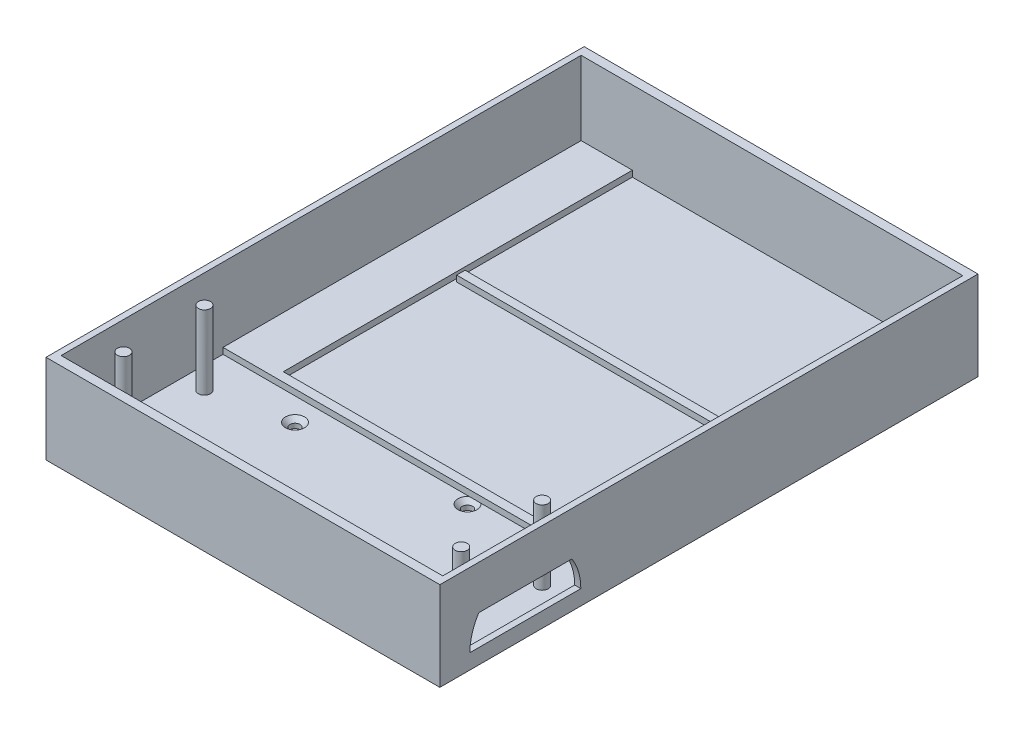
SolidWorks part; units mm, degrees
ref_plane "Front Plane" through (0, 0, 0) normal (0, 0, 1) x (1, 0, 0)
ref_plane "Top Plane" through (0, 0, 0) normal (0, 1, 0) x (1, 0, 0)
ref_plane "Right Plane" through (0, 0, 0) normal (1, 0, 0) x (0, 0, -1)
sketch "Sketch1" plane through (0, 0, 0) normal (0, 1, 0) x (1, 0, 0)
  line L0 (108.1468, 39.1756) -> (131.5768, 39.1756)
  line L1 (23.9468, 39.1756) -> (108.1468, 39.1756)
  line L2 (23.9468, 39.1756) -> (23.9468, -17.2844)
  line L3 (23.9468, -17.2844) -> (108.1468, -17.2844)
  line L4 (108.1468, 39.1756) -> (108.1468, -17.2844)
  line L5 (23.9468, 39.1756) -> (6.9568, 39.1756)
  line L6 (6.9568, 39.1756) -> (131.5768, 39.1756)
  line L7 (6.9568, 39.1756) -> (3.9568, 39.1756)
  line L8 (131.5768, 39.1756) -> (134.5768, 39.1756)
  line L9 (134.5768, 39.1756) -> (134.5768, 42.1756)
  line L10 (3.9568, 39.1756) -> (134.5768, 39.1756)
  line L11 (3.9568, 39.1756) -> (3.9568, -17.083)
  line L12 (3.9568, -17.083) -> (134.5768, -17.083)
  line L13 (134.5768, 39.1756) -> (134.5768, -17.083)
  line L14 (3.9568, -17.083) -> (3.9568, -20.083)
  line L15 (134.5768, 42.1756) -> (3.9568, 42.1756)
  line L16 (134.5768, 42.1756) -> (134.5768, 39.1756)
  line L17 (134.5768, 39.1756) -> (3.9568, 39.1756)
  line L18 (3.9568, 42.1756) -> (3.9568, 39.1756)
  line L19 (3.9568, -20.083) -> (3.9568, -76.583)
  line L20 (3.9568, -17.083) -> (134.5768, -17.083)
  line L21 (3.9568, -17.083) -> (3.9568, -20.083)
  line L22 (3.9568, -20.083) -> (134.5768, -20.083)
  line L23 (134.5768, -17.083) -> (134.5768, -20.083)
  line L24 (23.9468, 39.1756) -> (23.9468, -76.583)
  line L25 (3.9568, -76.583) -> (134.5768, -76.583)
  line L26 (3.9568, -76.583) -> (3.9568, -20.083)
  line L27 (3.9568, -20.083) -> (134.5768, -20.083)
  line L28 (134.5768, -76.583) -> (134.5768, -20.083)
  line L29 (3.9568, -76.583) -> (134.5768, -76.583)
  line L30 (3.9568, -76.583) -> (3.9568, -79.583)
  line L31 (3.9568, -79.583) -> (134.5768, -79.583)
  line L32 (134.5768, -76.583) -> (134.5768, -79.583)
  line L33 (3.9568, -79.583) -> (134.5768, -79.583)
  line L34 (3.9568, -79.583) -> (3.9568, -133.283)
  line L35 (3.9568, -133.283) -> (134.5768, -133.283)
  line L36 (134.5768, -79.583) -> (134.5768, -133.283)
  line L37 (3.9568, -133.283) -> (134.5768, -133.283)
  line L38 (3.9568, -133.283) -> (3.9568, -136.283)
  line L39 (3.9568, -136.283) -> (134.5768, -136.283)
  line L40 (134.5768, -133.283) -> (134.5768, -136.283)
  line L41 (108.1468, -17.2844) -> (108.1468, -76.583)
  line L42 (108.1468, -67.5003) -> (109.1468, -67.5003)
  line L43 (108.1468, 39.1756) -> (109.1468, 39.1756)
  line L44 (108.1468, 39.1756) -> (108.1468, -76.583)
  line L45 (108.1468, -76.583) -> (109.1468, -76.583)
  line L46 (109.1468, 39.1756) -> (109.1468, -76.583)
  line L47 (23.9468, -33.892) -> (22.9468, -33.892)
  line L48 (109.1468, -76.583) -> (134.5768, -76.583)
  line L49 (109.1468, -76.583) -> (109.1468, 39.1756)
  line L50 (109.1468, 39.1756) -> (134.5768, 39.1756)
  line L51 (134.5768, -76.583) -> (134.5768, 39.1756)
  line L52 (23.9468, -76.583) -> (22.9468, -76.583)
  line L53 (23.9468, -76.583) -> (23.9468, 39.1756)
  line L54 (23.9468, 39.1756) -> (22.9468, 39.1756)
  line L55 (22.9468, -76.583) -> (22.9468, 39.1756)
  line L57 (109.1468, 39.1756) -> (134.5768, 39.1756)
  line L58 (109.1468, 39.1756) -> (109.1468, -76.583)
  line L59 (109.1468, -76.583) -> (134.5768, -76.583)
  line L60 (134.5768, 39.1756) -> (134.5768, -76.583)
  line L61 (3.9568, 39.1756) -> (22.9468, 39.1756)
  line L62 (3.9568, 39.1756) -> (3.9568, -76.583)
  line L63 (3.9568, -76.583) -> (22.9468, -76.583)
  line L64 (22.9468, 39.1756) -> (22.9468, -76.583)
  dimension "D1" = 84.2
  dimension "D2" = 56.46
  dimension "D3" = 23.43
  dimension "D4" = 16.99
  dimension "D5" = 3
  dimension "D6" = 3
  dimension "D7" = 3
  dimension "D8" = 3
  dimension "D9" = 56.5
  dimension "D10" = 3
  dimension "D11" = 53.7
  dimension "D12" = 3
  dimension "D13" = 1
  dimension "D14" = 1
extrude "Boss-Extrude1" add sketch "Sketch1" along normal blind 2 contours L40 L35 L38 L39 | L32 L25 L29 L30 L31 | L22 L46 L25 L28 | L25 L55 L22 L19 | L12 L55 L17 L7 L11 | L17 L46 L20 L13 L8 | L22 L55 L12 L14 | L20 L46 L22 L23 | L41 L3 L24 L22 | L15 L18 L7 L17 L5 L1 L0 L8 L9
sketch "Sketch2" plane through (0, 0, 0) normal (0, -1, 0) x (1, 0, 0)
  line L1 (3.9568, 136.283) -> (134.5768, 136.283)
  line L2 (3.9568, 136.283) -> (3.9568, -42.1756)
  line L3 (3.9568, -42.1756) -> (134.5768, -42.1756)
  line L4 (134.5768, 136.283) -> (134.5768, -42.1756)
extrude "Boss-Extrude2" add sketch "Sketch2" along normal blind 3
sketch "Sketch5" plane through (0, 0, 0) normal (0, 1, 0) x (1, 0, 0)
  line L0 (69.2668, -79.583) -> (103.5341, -79.583)
  line L1 (3.9568, -79.583) -> (134.5768, -79.583) construction
  line L2 (69.2668, -79.583) -> (34.9668, -79.583)
  line L3 (103.5341, -79.583) -> (103.5341, -130.283)
  line L4 (103.5341, -130.283) -> (88.2341, -130.283)
  line L5 (103.5341, -130.283) -> (34.9668, -130.283)
  line L6 (103.5341, -130.283) -> (103.5341, -79.583)
  line L7 (103.5341, -79.583) -> (34.9668, -79.583)
  line L8 (34.9668, -130.283) -> (34.9668, -79.583)
  line L9 (37.4341, -130.283) -> (37.4341, -115.083)
  line L10 (88.2341, -130.283) -> (37.4341, -130.283)
  line L11 (88.2341, -130.283) -> (88.2341, -132.2622)
  line L12 (88.2341, -132.2622) -> (37.4341, -132.2622)
  line L13 (37.4341, -130.283) -> (37.4341, -132.2622)
  line L14 (37.4341, -115.083) -> (37.4341, -87.183)
  line L15 (37.4341, -87.183) -> (37.4341, -82.083)
  line L16 (37.4341, -82.083) -> (103.5341, -82.083)
  line L17 (89.5341, -82.083) -> (89.5341, -130.283)
  line L18 (89.5341, -82.083) -> (103.5341, -82.083)
  line L19 (89.5341, -82.083) -> (89.5341, -89.2672)
  line L20 (89.5341, -89.2672) -> (103.5341, -89.2672)
  line L21 (103.5341, -82.083) -> (103.5341, -89.2672)
  line L22 (88.2341, -130.283) -> (88.2341, -82.083)
  line L23 (88.2341, -82.083) -> (88.2341, -106.183)
  line L24 (88.2341, -106.183) -> (89.5341, -106.183)
  dimension "D1" = 34.2673
  dimension "D2" = 34.3
  dimension "D3" = 50.7
  dimension "D4" = 15.3
  dimension "D5" = 50.8
  dimension "D6" = 15.2
  dimension "D7" = 27.9
  dimension "D8" = 5.1
  dimension "D9" = 14
sketch3d "3DSketch1" plane through (0, 0, 0) normal (0, 0, 1) x (1, 0, 0)
hole_wizard "CSK for M3 Countersunk Flat Head Screw1" positions "3DSketch4" profile "Sketch8" countersink size "M3" standard "ISO" end condition through all
sketch3d "3DSketch4"
  point P0 (88.2341, 0, 130.283)
  point P3 (37.4341, 0, 115.083)
  point P6 (37.4341, 0, 87.183)
  point P9 (89.5341, 0, 82.083)
sketch "Sketch8" plane through (88.2341, 0, 130.283) normal (1, 0, 0) x (0, 0, 1)
  line L0 (0, 0) -> (0, 3)
  line L1 (0, 3) -> (1.7, 3)
  line L2 (1.7, 3) -> (1.7, 1.45)
  line L3 (1.7, 1.45) -> (3.15, 0)
  line L5 (3.15, 0) -> (0, 0)
  line L6 (-1.7, 1.45) -> (-3.15, 0) construction
  line L11 (0, -6.35) -> (0, 107.95) construction
  dimension "Thru Hole Dia." = 3.4
  dimension "Thru Hole Depth" = 3
  dimension "Near C'Sink Dia." = 6.3
  dimension "Near C'Sink Angle" = 90
sketch "Sketch9" plane through (0, 0, 0) normal (0, 1, 0) x (1, 0, 0)
  line L0 (91.4505, -79.583) -> (134.5768, -79.583) construction
  line L1 (134.5768, -133.283) -> (132.529, -133.283)
  line L2 (134.5768, -133.283) -> (134.5768, -79.583)
  line L3 (134.5768, -79.583) -> (132.529, -79.583)
  line L4 (132.529, -133.283) -> (132.529, -79.583)
  line L5 (3.9568, -79.583) -> (87.6177, -79.583) construction
  line L6 (3.9568, -133.283) -> (5.9568, -133.283)
  line L7 (3.9568, -133.283) -> (3.9568, -79.583)
  line L8 (3.9568, -79.583) -> (5.9568, -79.583)
  line L9 (5.9568, -133.283) -> (5.9568, -79.583)
  dimension "D1" = 2.0478
  dimension "D2" = 2
extrude "Boss-Extrude3" add sketch "Sketch9" along normal blind 24
sketch "Sketch10" plane through (0, 2, 0) normal (0, 1, 0) x (1, 0, 0)
  line L1 (134.5768, -136.283) -> (3.9568, -136.283)
  line L2 (134.5768, -136.283) -> (134.5768, -133.283)
  line L3 (134.5768, -133.283) -> (3.9568, -133.283)
  line L4 (3.9568, -136.283) -> (3.9568, -133.283)
extrude "Boss-Extrude4" add sketch "Sketch10" along normal blind 22
sketch "Sketch11" plane through (134.5768, 0, 0) normal (1, 0, 0) x (0, 0, -1)
  line L0 (-79.583, 2) -> (-136.283, 2)
  line L1 (-136.283, 24) -> (-136.283, -3) construction
  line L2 (-107.933, 24) -> (-107.933, 2)
  line L3 (-136.283, 24) -> (-79.583, 24) construction
  line L5 (-107.933, 2) -> (-126.333, 2)
  line L6 (-107.933, 2) -> (-107.933, 12)
  line L7 (-107.933, 12) -> (-126.333, 12)
  line L8 (-126.333, 2) -> (-126.333, 12)
  line L9 (-107.933, 2) -> (-89.533, 2)
  line L10 (-107.933, 2) -> (-107.933, 12)
  line L11 (-107.933, 12) -> (-89.533, 12)
  line L12 (-89.533, 2) -> (-89.533, 12)
  circle A0 centre (-107.933, 2) radius 18.4
  dimension "D1" = 18.4
  dimension "D2" = 18.4
  dimension "D3" = 10
extrude "Cut-Extrude1" cut sketch "Sketch11" against normal blind 22 contours L7 A0 L0 L2 | L0 A0 L11 L2
sketch "Sketch12" plane through (0, 2, 0) normal (0, 1, 0) x (1, 0, 0)
  line L0 (3.9568, 42.1756) -> (3.9568, -79.583) construction
  line L1 (134.5768, 42.1756) -> (3.9568, 42.1756)
  line L2 (134.5768, 42.1756) -> (134.5768, 39.1756)
  line L3 (134.5768, 39.1756) -> (3.9568, 39.1756)
  line L4 (3.9568, 42.1756) -> (3.9568, 39.1756)
  line L5 (5.9568, -79.583) -> (132.529, -79.583) construction
  line L6 (134.5768, 42.1756) -> (132.529, 42.1756)
  line L7 (134.5768, 42.1756) -> (134.5768, -79.583)
  line L8 (134.5768, -79.583) -> (132.529, -79.583)
  line L9 (132.529, 42.1756) -> (132.529, -79.583)
  line L10 (3.9568, 42.1756) -> (5.9568, 42.1756)
  line L11 (3.9568, 42.1756) -> (3.9568, -79.583)
  line L12 (3.9568, -79.583) -> (5.9568, -79.583)
  line L13 (5.9568, 42.1756) -> (5.9568, -79.583)
  line M3 (22.9468, 39.1756) -> (109.1468, 39.1756)
extrude "Boss-Extrude5" add sketch "Sketch12" along normal blind 22 contours L1 L13 L3 L9 M3
sketch "Sketch13" plane through (0, 0, 0) normal (0, 1, 0) x (1, 0, 0)
  line L0 (34.9668, -79.583) -> (5.9568, -79.583)
  line L1 (5.9568, -133.283) -> (5.9568, -79.583) construction
  line L2 (5.9568, -79.583) -> (87.6177, -79.583) construction
  line L3 (5.9568, -79.583) -> (20.4618, -79.583)
  line L4 (20.4618, -79.583) -> (20.4618, -133.283)
  line L5 (5.9568, -133.283) -> (87.2736, -133.283) construction
  line L6 (20.4618, -79.583) -> (20.4618, -106.433)
  line L7 (20.4618, -106.433) -> (20.4618, -133.283)
  line L8 (20.4618, -79.583) -> (5.9568, -79.583)
  line L9 (13.2093, -79.583) -> (13.2093, -133.283)
  line L10 (13.2093, -106.433) -> (13.2093, -79.583)
  line L11 (13.2093, -93.008) -> (15.5863, -93.008)
  line L12 (13.2093, -106.433) -> (13.2093, -133.283)
  line L13 (13.2093, -119.858) -> (15.5863, -119.858)
  line L14 (13.2093, -79.583) -> (5.9568, -79.583)
  line L15 (132.529, -79.583) -> (125.229, -79.583)
  line L16 (5.9568, -79.583) -> (13.2093, -79.583)
  line L17 (5.9568, -79.583) -> (5.9568, -82.8483)
  line L18 (5.9568, -82.8483) -> (13.2093, -82.8483)
  line L19 (13.2093, -79.583) -> (13.2093, -82.8483)
  line L20 (91.4505, -79.583) -> (132.529, -79.583) construction
  line L21 (125.229, -79.583) -> (125.229, -133.283)
  line L22 (89.1946, -133.283) -> (132.529, -133.283) construction
  line L23 (125.229, -133.283) -> (125.229, -106.433)
  line L24 (125.229, -106.433) -> (125.229, -93.008)
  line L25 (125.229, -93.008) -> (125.229, -119.858)
  line L26 (125.229, -119.858) -> (13.2093, -119.858)
  line L28 (13.2093, -93.008) -> (125.229, -93.008)
  line L29 (13.2093, -93.008) -> (13.2093, -119.858)
  line L30 (13.2093, -119.858) -> (125.229, -119.858)
  line L31 (125.229, -93.008) -> (125.229, -119.858)
  circle A0 centre (13.2093, -93.008) radius 2
  circle A1 centre (13.2093, -119.858) radius 2
  circle A2 centre (125.229, -93.008) radius 2
  circle A3 centre (125.229, -119.858) radius 2
extrude "Boss-Extrude6" add sketch "Sketch13" along normal blind 24.5 contours L23 A3 L31 | L26 A3 L23 | L31 A3 L26 | L12 A1 L13 | L13 A1 L29 | L29 A1 L12 | L10 A0 L11 | L11 A0 L9 | L9 A0 L10 | A2
sketch "Sketch14" plane through (0, 24, 0) normal (0, 1, 0) x (1, 0, 0)
  line L0 (3.9568, 42.1756) -> (3.9568, -136.283) construction
  line L1 (134.5768, 42.1756) -> (3.9568, 42.1756)
  line L2 (134.5768, 42.1756) -> (134.5768, 39.1756)
  line L3 (134.5768, 39.1756) -> (3.9568, 39.1756)
  line L4 (3.9568, 42.1756) -> (3.9568, 39.1756)
  line L5 (3.9568, -136.283) -> (134.5768, -136.283) construction
  line L6 (3.9568, 42.1756) -> (5.9568, 42.1756)
  line L7 (3.9568, 42.1756) -> (3.9568, -136.283)
  line L8 (3.9568, -136.283) -> (5.9568, -136.283)
  line L9 (5.9568, 42.1756) -> (5.9568, -136.283)
  line L11 (3.9568, -136.283) -> (132.529, -136.283)
  line L12 (3.9568, -136.283) -> (3.9568, -133.283)
  line L13 (3.9568, -133.283) -> (132.529, -133.283)
  line L14 (132.529, -136.283) -> (132.529, -133.283)
  line L15 (132.529, -136.283) -> (134.5768, -136.283)
  line L16 (132.529, -136.283) -> (132.529, 39.1756)
  line L17 (132.529, 39.1756) -> (134.5768, 39.1756)
  line L18 (134.5768, -136.283) -> (134.5768, 39.1756)
sketch "Sketch15" plane through (0, 24, 0) normal (0, 1, 0) x (1, 0, 0)
  line L1 (134.5768, 42.1756) -> (132.529, 42.1756)
  line L2 (134.5768, 42.1756) -> (134.5768, -136.283)
  line L3 (134.5768, -136.283) -> (132.529, -136.283)
  line L4 (132.529, 42.1756) -> (132.529, -136.283)
  line L5 (134.5768, 42.1756) -> (3.9568, 42.1756)
  line L6 (134.5768, 42.1756) -> (134.5768, 39.1756)
  line L7 (134.5768, 39.1756) -> (3.9568, 39.1756)
  line L8 (3.9568, 42.1756) -> (3.9568, 39.1756)
  line L9 (5.9568, 42.1756) -> (3.9568, 42.1756)
  line L10 (5.9568, 42.1756) -> (5.9568, -136.283)
  line L11 (5.9568, -136.283) -> (3.9568, -136.283)
  line L12 (3.9568, 42.1756) -> (3.9568, -136.283)
  line L13 (3.9568, -136.283) -> (132.529, -136.283)
  line L14 (3.9568, -136.283) -> (3.9568, -133.283)
  line L15 (3.9568, -133.283) -> (132.529, -133.283)
  line L16 (132.529, -136.283) -> (132.529, -133.283)
  line M1 (5.9568, 39.1756) -> (132.529, 39.1756)
  line M2 (132.529, 39.1756) -> (132.529, -133.283)
  line M3 (132.529, -133.283) -> (5.9568, -133.283)
  line M4 (5.9568, -133.283) -> (5.9568, 39.1756)
  line M5 (134.5768, -136.283) -> (134.5768, 42.1756)
  line M6 (134.5768, 42.1756) -> (3.9568, 42.1756)
  line M7 (3.9568, 42.1756) -> (3.9568, -136.283)
  line M8 (3.9568, -136.283) -> (134.5768, -136.283)
extrude "Boss-Extrude7" add sketch "Sketch15" along normal blind 2.5 contours L10 L4 M6 M1 | L15 L7 M7 M4 | L10 L5 L7 M7 | L7 L2 L4 M6 | L7 L4 M5 M2 M8 | L15 L12 L10 M8 | L10 L4 M3 M8
